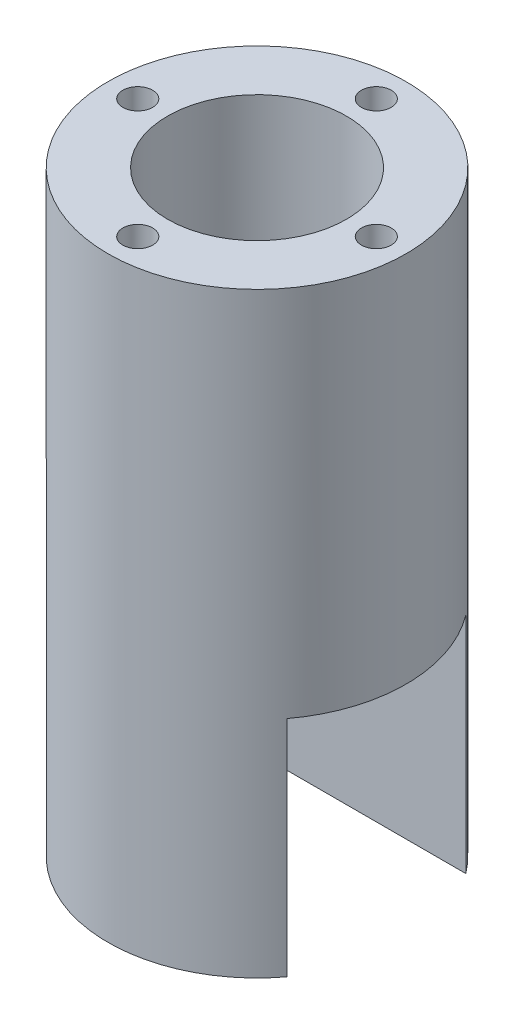
SolidWorks part; units mm, degrees
ref_plane "前视基准面" through (0, 0, 0) normal (0, 0, 1) x (1, 0, 0)
ref_plane "上视基准面" through (0, 0, 0) normal (0, 1, 0) x (1, 0, 0)
ref_plane "右视基准面" through (0, 0, 0) normal (1, 0, 0) x (0, 0, -1)
sketch "草图1" plane through (0, 0, 0) normal (0, 1, 0) x (1, 0, 0)
  circle A0 centre (0, 0) radius 6
  circle A1 centre (0, 0) radius 10
  dimension "D1" = 20
  dimension "D2" = 12
extrude "凸台-拉伸1" add sketch "草图1" along normal blind 40
sketch "草图2" plane through (0, 40, 0) normal (0, 1, 0) x (1, 0, 0)
  line L0 (-12.3651, 0) -> (0, 0) construction
  line L1 (0, 0) -> (14.3557, 0) construction
  line L2 (0, 0) -> (9.7715, 9.7715) construction
  line L3 (0, 0) -> (0, 10.7764) construction
  circle A0 centre (-8, 0) radius 1
  circle A1 centre (8, 0) radius 1
  circle A2 centre (0, 8) radius 1
  circle A3 centre (0, -8) radius 1
  dimension "D2" = 2
  dimension "D1" = 8
extrude "切除-拉伸1" cut sketch "草图2" against normal blind 2
sketch "草图3" plane through (0, 0, 0) normal (1, 0, 0) x (0, 0, -1)
  line L0 (0, 10.6577) -> (0, -2.2146) construction
  line L1 (-6, 0) -> (6, 0)
  line L2 (-10, 0) -> (10, 0) construction
  line L3 (6, 0) -> (6, 15)
  line L4 (6, 15) -> (-6, 15)
  line L5 (-6, 0) -> (-6, 15)
  point P10 (0, 0)
  point P11 (0, 15)
  dimension "D1" = 15
  dimension "D2" = 6
extrude "切除-拉伸2" cut sketch "草图3" against normal through all both and the other way through all
